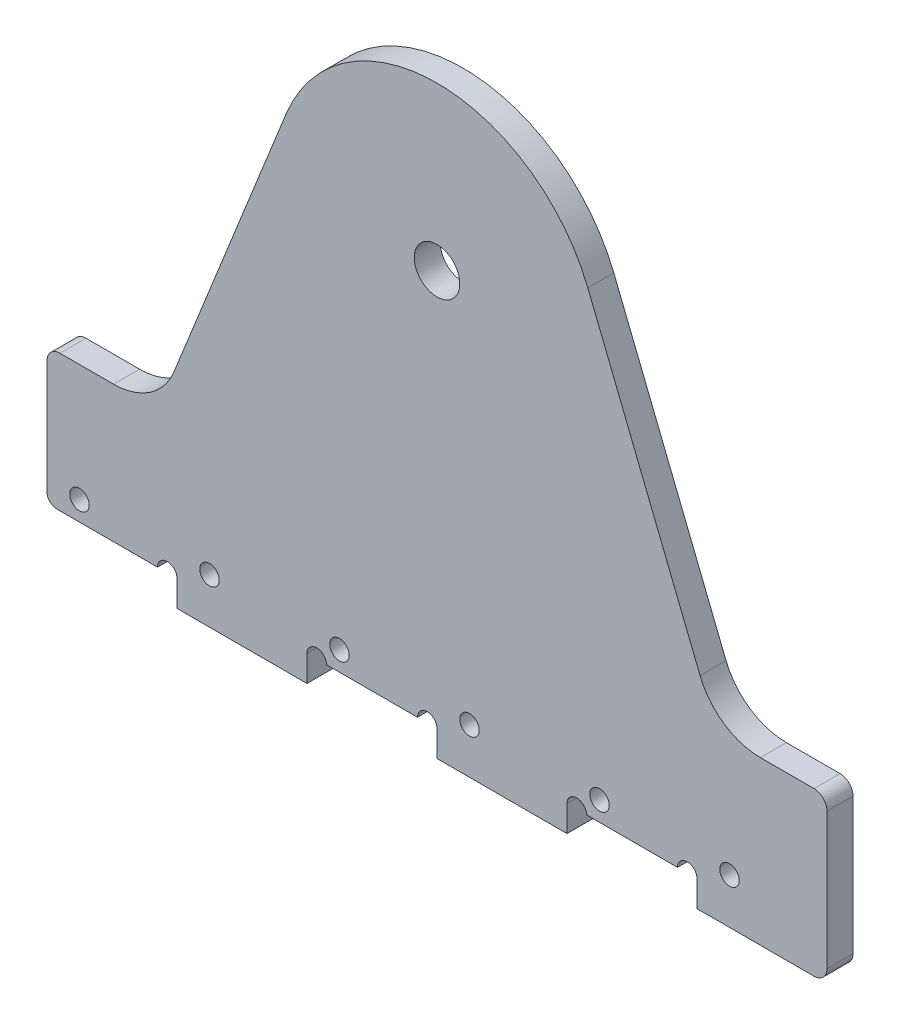
SolidWorks part; units mm, degrees
ref_plane "前视基准面" through (0, 0, 0) normal (0, 0, 1) x (1, 0, 0)
ref_plane "上视基准面" through (0, 0, 0) normal (0, 1, 0) x (1, 0, 0)
ref_plane "右视基准面" through (0, 0, 0) normal (1, 0, 0) x (0, 0, -1)
other "Configuration Table"
sketch "草图1" plane through (0, 0, 0) normal (0, 0, 1) x (1, 0, 0)
  line L0 (-23.2017, 9.3102) -> (-42.9886, -40)
  line L1 (-42.9886, -40) -> (-60, -40)
  line L2 (-60, -40) -> (-60, -65)
  line L3 (-60, -65) -> (60, -65)
  line L4 (60, -65) -> (60, -40)
  line L5 (60, -40) -> (42.9886, -40)
  line L6 (23.2017, 9.3102) -> (42.9886, -40)
  circle A2 centre (0, 0) radius 25
  circle A3 centre (0, 0) radius 3.5
  dimension "D1" = 7
  dimension "D2" = 50
  dimension "D3" = 120
  dimension "D4" = 65
  dimension "D5" = 17.0114
  dimension "D6" = 25
extrude "凸台-拉伸1" add sketch "草图1" along normal blind 4
fillet "圆角1" radius 10 2 edges at (-42.9886, -40, 2) (42.9886, -40, 2)
fillet "圆角2" radius 2 4 edges at (60, -40, 2) (60, -65, 2) (-60, -65, 2) (-60, -40, 2)
sketch "草图2" plane through (0, 0, 4) normal (0, 0, 1) x (1, 0, 0)
  line L2 (-58, -65) -> (58, -65) construction
  line L3 (-60, -65) -> (-40, -65)
  line L4 (-60, -65) -> (-60, -61)
  line L5 (-60, -61) -> (-40, -61)
  line L6 (-40, -65) -> (-40, -61)
  line L7 (-20, -65) -> (0, -65)
  line L8 (-20, -65) -> (-20, -61)
  line L9 (-20, -61) -> (0, -61)
  line L10 (0, -65) -> (0, -61)
  line L11 (-60, -42) -> (-60, -63) construction
  line L12 (20, -65) -> (40, -65)
  line L13 (20, -65) -> (20, -61)
  line L14 (20, -61) -> (40, -61)
  line L15 (40, -65) -> (40, -61)
  arc A0 (-40, -61) -> (-43, -61) centre (-41.5, -61) ccw
  arc A1 (-20, -61) -> (-17, -61) centre (-18.5, -61) cw
  arc A2 (0, -61) -> (-3, -61) centre (-1.5, -61) ccw
  arc A3 (20, -61) -> (23, -61) centre (21.5, -61) cw
  arc A4 (40, -61) -> (37, -61) centre (38.5, -61) ccw
  line M24 (-60, -42) -> (-60, -63)
  arc M25 (-60, -63) -> (-58, -65) centre (-58, -63) ccw
  line M26 (-58, -65) -> (58, -65)
  dimension "D7" = 1.5
  dimension "D8" = 1.5
  dimension "D9" = 1.5
  dimension "D10" = 1.5
  dimension "D11" = 1.5
  dimension "D1" = 20
  dimension "D2" = 20
  dimension "D3" = 20
  dimension "D4" = 20
  dimension "D5" = 20
  dimension "D6" = 4
extrude "切除-拉伸1" cut sketch "草图2" against normal blind 10 contours L5 A0 | L6 L5 M26 M24 M25 | A1 L9 | L10 L9 L8 M26 | L9 A2 | A3 L14 | L15 L14 L13 M26 | L14 A4
fillet "圆角3" radius 1.5 1 edges at (-60, -61, 2)
sketch "草图3" plane through (0, 0, 4) normal (0, 0, 1) x (1, 0, 0)
  line L0 (-58.5, -61) -> (-43, -61) construction
  line L1 (-60, -42) -> (-60, -59.5) construction
  circle A0 centre (-55, -58) radius 1.5
  circle A1 centre (-35, -58) radius 1.5
  circle A2 centre (-15, -58) radius 1.5
  circle A3 centre (5, -58) radius 1.5
  circle A4 centre (25, -58) radius 1.5
  circle A5 centre (45, -58) radius 1.5
  dimension "D3" = 3
  dimension "D1" = 3
  dimension "D2" = 5
  dimension "D5" = 20
  dimension "D4" = 6
extrude "切除-拉伸2" cut sketch "草图3" against normal blind 4
